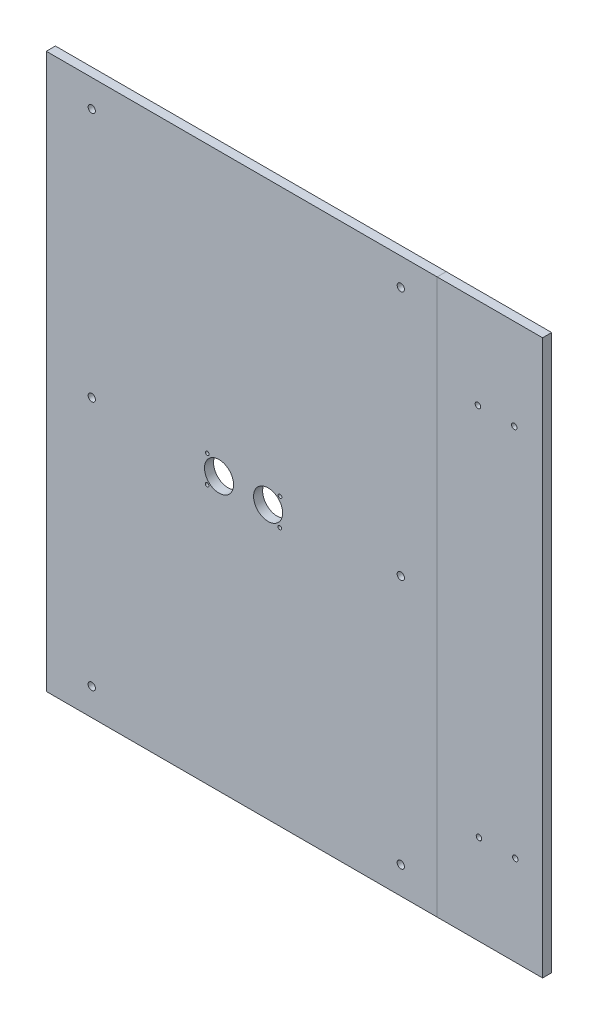
SolidWorks part; units mm, degrees
ref_plane "Plan de face" through (0, 0, 0) normal (0, 0, 1) x (1, 0, 0)
ref_plane "Plan de dessus" through (0, 0, 0) normal (0, 1, 0) x (1, 0, 0)
ref_plane "Plan de droite" through (0, 0, 0) normal (1, 0, 0) x (0, 0, -1)
sketch "Esquisse1" plane through (0, 0, 0) normal (0, 0, 1) x (1, 0, 0)
  line L1 (0, 0) -> (215, 0)
  line L2 (0, 0) -> (0, 305)
  line L3 (0, 305) -> (215, 305)
  line L4 (215, 0) -> (215, 305)
  dimension "D1" = 305
  dimension "D2" = 215
extrude "Boss.-Extru.1" add sketch "Esquisse1" along normal blind 5
sketch "Esquisse2" plane through (0, 0, 0) normal (0, 0, -1) x (-1, 0, 0)
  line L0 (-215, 0) -> (-215, 305) construction
  line L1 (-215, 305) -> (0, 305) construction
  line L2 (0, 305) -> (0, 0) construction
  line L3 (0, 0) -> (-215, 0) construction
  circle A0 centre (-195, 290) radius 2
  circle A1 centre (-25, 290) radius 2
  circle A2 centre (-25, 15) radius 2
  circle A3 centre (-195, 15) radius 2
  circle A4 centre (-195, 152.5) radius 2
  circle A5 centre (-25, 152.5) radius 2
  dimension "D1" = 4
  dimension "D2" = 4
  dimension "D3" = 4
  dimension "D4" = 4
  dimension "D5" = 20
  dimension "D6" = 20
  dimension "D8" = 15
  dimension "D9" = 25
  dimension "D10" = 15
  dimension "D11" = 25
  dimension "D12" = 15
  dimension "D13" = 4
  dimension "D14" = 4
  dimension "D15" = 152.5
  dimension "D16" = 152.5
  dimension "D17" = 20
  dimension "D18" = 25
  dimension "D7" = 15
extrude "Enlèv. mat.-Extru.1" cut sketch "Esquisse2" against normal blind 5
sketch "Esquisse3" plane through (0, 0, 0) normal (0, 0, -1) x (-1, 0, 0)
  line L1 (-215, 305) -> (-273, 305)
  line L2 (-215, 305) -> (-215, 0)
  line L3 (-215, 0) -> (-273, 0)
  line L4 (-273, 305) -> (-273, 0)
  dimension "D1" = 58
extrude "Boss.-Extru.2" add sketch "Esquisse3" against normal blind 5 separate body
sketch "Esquisse4" plane through (0, 0, 0) normal (0, 0, -1) x (-1, 0, 0)
  circle A0 centre (-237.4, 255) radius 1.5
  circle A1 centre (-257.4, 255) radius 1.5
  dimension "D1" = 3
  dimension "D2" = 3
extrude "Enlèv. mat.-Extru.3" cut sketch "Esquisse4" against normal through all
sketch "Esquisse5" plane through (0, 0, 5) normal (0, 0, 1) x (1, 0, 0)
  circle A0 centre (238, 49.5) radius 1.5
  circle A1 centre (258, 49.5) radius 1.5
  dimension "D1" = 3
  dimension "D2" = 3
extrude "Enlèv. mat.-Extru.4" cut sketch "Esquisse5" against normal through all
sketch "Esquisse6" plane through (0, 0, 0) normal (0, 0, -1) x (-1, 0, 0)
  line L0 (0, 305) -> (0, 0) construction
  line L1 (0, 0) -> (-215, 0) construction
  circle A0 centre (-122, 150) radius 8
  circle A1 centre (-95, 150) radius 8
  dimension "D1" = 16
  dimension "D2" = 16
  dimension "D3" = 27
  dimension "D4" = 95
  dimension "D5" = 150
  dimension "D6" = 150
extrude "Enlèv. mat.-Extru.5" cut sketch "Esquisse6" against normal through all
sketch "Esquisse7" plane through (0, 0, 0) normal (0, 0, -1) x (-1, 0, 0)
  circle A0 centre (-128.548, 157.2855) radius 1
  circle A1 centre (-128.452, 142.2855) radius 1
  circle A2 centre (-88.548, 157.7146) radius 1
  circle A3 centre (-88.4519, 142.7146) radius 1
  circle A9 centre (-122, 150) radius 8 construction
  circle A10 centre (-95, 150) radius 8 construction
  dimension "D1" = 2
  dimension "D2" = 2
  dimension "D3" = 2
  dimension "D4" = 2
  dimension "D5" = 15
  dimension "D6" = 15
  dimension "D7" = 34.33
  dimension "D8" = 34.33
  dimension "D9" = 40
  dimension "D10" = 34.33
  dimension "D11" = 34.33
  dimension "D12" = 40
extrude "Enlèv. mat.-Extru.7" cut sketch "Esquisse7" against normal through all
